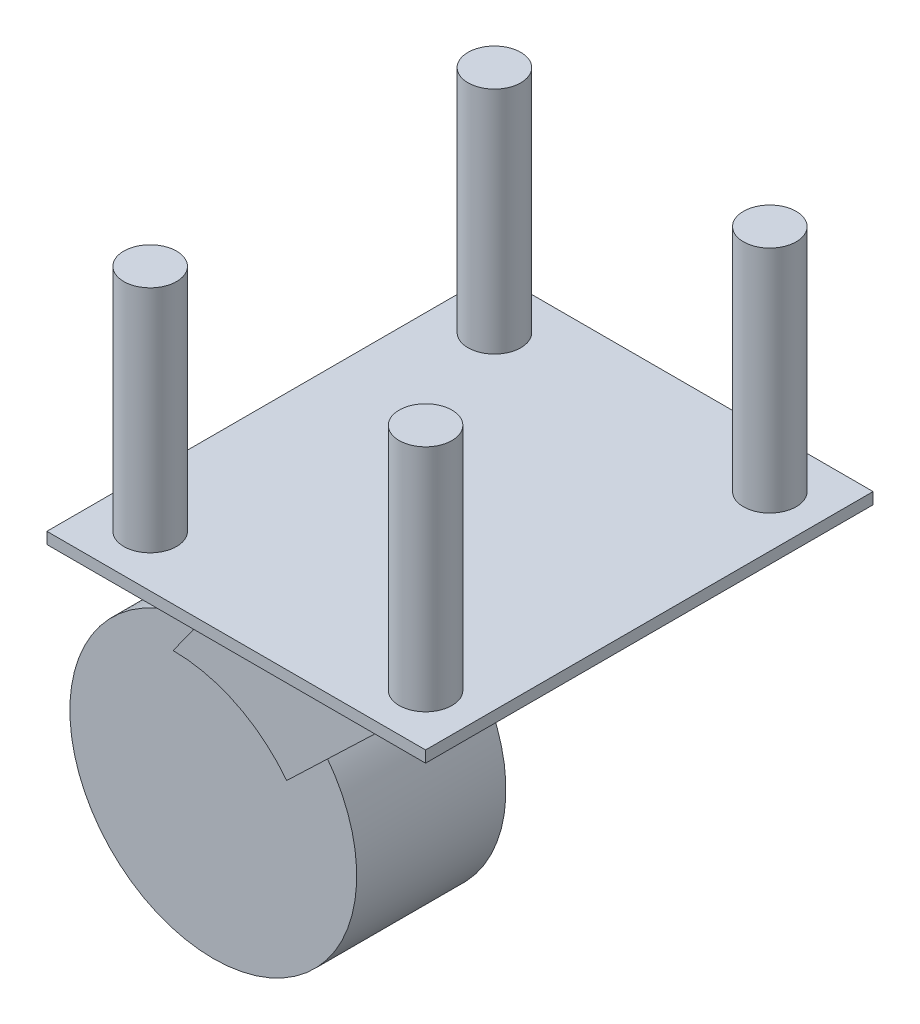
SolidWorks part; units mm, degrees
ref_plane "前视基准面" through (0, 0, 0) normal (0, 0, 1) x (1, 0, 0)
ref_plane "上视基准面" through (0, 0, 0) normal (0, 1, 0) x (1, 0, 0)
ref_plane "右视基准面" through (0, 0, 0) normal (1, 0, 0) x (0, 0, -1)
other "Configuration Table"
sketch "草图1" plane through (0, 0, 0) normal (0, 1, 0) x (1, 0, 0)
  line L1 (-16.5, 19.5) -> (16.5, 19.5)
  line L2 (-16.5, 19.5) -> (-16.5, -19.5)
  line L3 (-16.5, -19.5) -> (16.5, -19.5)
  line L4 (16.5, 19.5) -> (16.5, -19.5)
  line L5 (-16.5, 19.5) -> (16.5, -19.5) construction
  line L6 (-16.5, -19.5) -> (16.5, 19.5) construction
  point P0 (0, 0)
  dimension "D1" = 33
  dimension "D2" = 39
extrude "凸台-拉伸1" add sketch "草图1" along normal blind 1
sketch "草图2" plane through (0, 0, 0) normal (0, 0, 1) x (1, 0, 0)
  line L1 (-16.5, 1) -> (16.5, 1) construction
  circle A0 centre (-15, -24.5) radius 12.5
  dimension "D1" = 25
  dimension "D2" = 38
  dimension "D3" = 15
extrude "凸台-拉伸2" add sketch "草图2" along normal mid plane 13 separate body
sketch "草图3" plane through (0, 0, 0) normal (0, 0, 1) x (1, 0, 0)
  line L0 (-12.5, 0) -> (-11.1119, -6.5745)
  line L2 (0, 0) -> (0, 11.7996) construction
  line L3 (-5.1045, -16.8626) -> (12.5, 0)
  line L4 (-11.1119, -6.5745) -> (-15, -12)
  line L5 (-12.5, 0) -> (12.5, 0)
  line L6 (-16.5, 0) -> (16.5, 0) construction
  circle A0 centre (-15, -24.5) radius 12.5 construction
  arc A1 (-5.1045, -16.8626) -> (-15, -12) centre (-15, -24.5) ccw
  dimension "D1" = 25
extrude "凸台-拉伸3" add sketch "草图3" along normal mid plane 20
sketch "草图4" plane through (0, 1, 0) normal (0, 1, 0) x (1, 0, 0)
  line L1 (-12, 15) -> (12, 15) construction
  line L2 (-12, 15) -> (-12, -15) construction
  line L3 (-12, -15) -> (12, -15) construction
  line L4 (12, 15) -> (12, -15) construction
  line L5 (-12, 15) -> (12, -15) construction
  line L6 (-12, -15) -> (12, 15) construction
  circle A0 centre (-12, 15) radius 2.3
  circle A1 centre (12, 15) radius 2.3
  circle A2 centre (-12, -15) radius 2.3
  circle A3 centre (12, -15) radius 2.3
  point P0 (0, 0)
  dimension "D3" = 4.6
  dimension "D1" = 24
  dimension "D2" = 30
extrude "凸台-拉伸4" add sketch "草图4" along normal blind 20
sketch "草图5" plane through (0, 0, 0) normal (0, -1, 0) x (1, 0, 0)
  circle A0 centre (0, 0) radius 12.5
  dimension "D1" = 25
extrude "切除-拉伸1" cut sketch "草图5" along normal blind 5 flip side to cut
